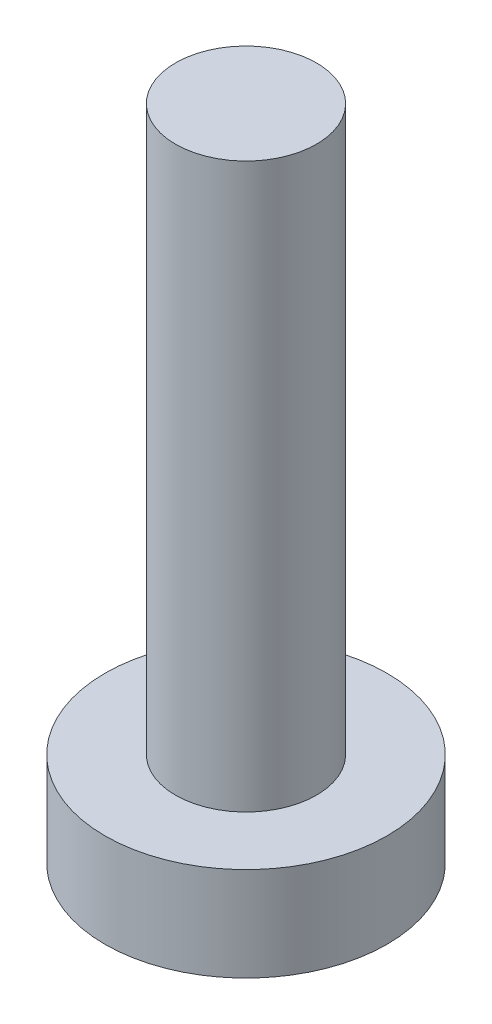
SolidWorks part; units mm, degrees
ref_plane "Front Plane" through (0, 0, 0) normal (0, 0, 1) x (1, 0, 0)
ref_plane "Top Plane" through (0, 0, 0) normal (0, 1, 0) x (1, 0, 0)
ref_plane "Right Plane" through (0, 0, 0) normal (1, 0, 0) x (0, 0, -1)
sketch "Sketch2" plane through (0, 0, 0) normal (0, 1, 0) x (1, 0, 0)
  circle A0 centre (0, 0) radius 3
extrude "Boss-Extrude1" add sketch "Sketch2" along normal blind 2
sketch "Sketch3" plane through (0, 2, 0) normal (0, 1, 0) x (1, 0, 0)
  circle A0 centre (0, 0) radius 1.5
extrude "Boss-Extrude2" add sketch "Sketch3" along normal blind 12
